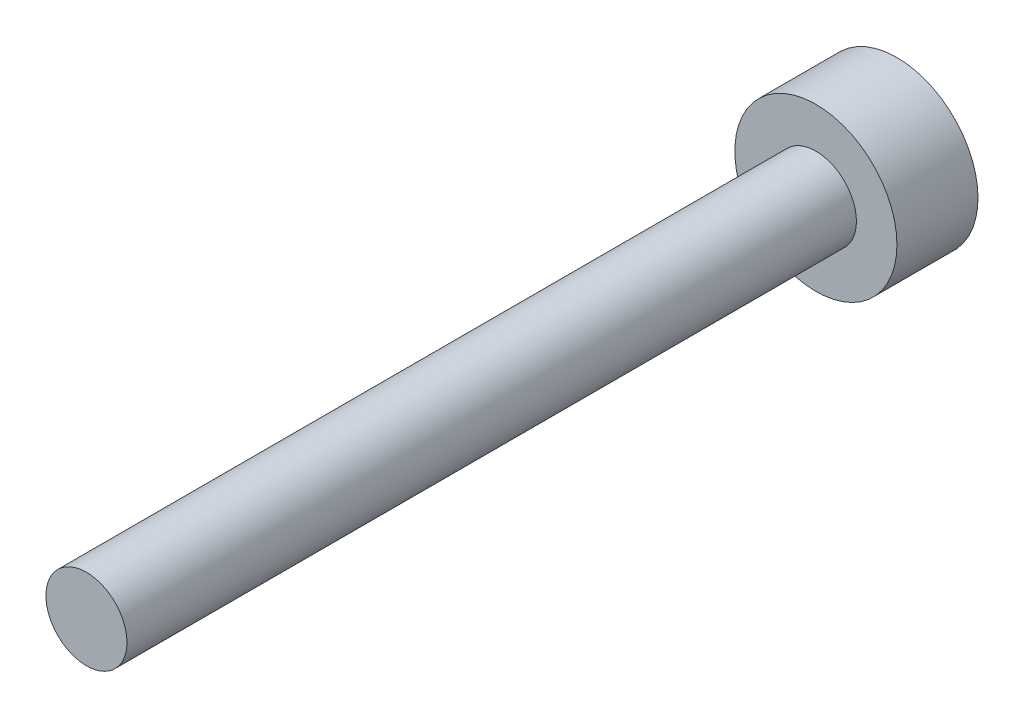
SolidWorks part; units mm, degrees
ref_plane "Alzado" through (0, 0, 0) normal (0, 0, 1) x (1, 0, 0)
ref_plane "Planta" through (0, 0, 0) normal (0, 1, 0) x (1, 0, 0)
ref_plane "Vista lateral" through (0, 0, 0) normal (1, 0, 0) x (0, 0, -1)
sketch "Croquis1" plane through (0, 0, 0) normal (0, 0, 1) x (1, 0, 0)
  circle A0 centre (13.1816, 0) radius 1.5
extrude "Saliente-Extruir1" add sketch "Croquis1" along normal blind 30
sketch "Croquis2" plane through (0, 0, 0) normal (0, 0, 1) x (1, 0, 0)
  circle A0 centre (13.1816, 0) radius 3
extrude "Saliente-Extruir2" add sketch "Croquis2" along normal blind 3
